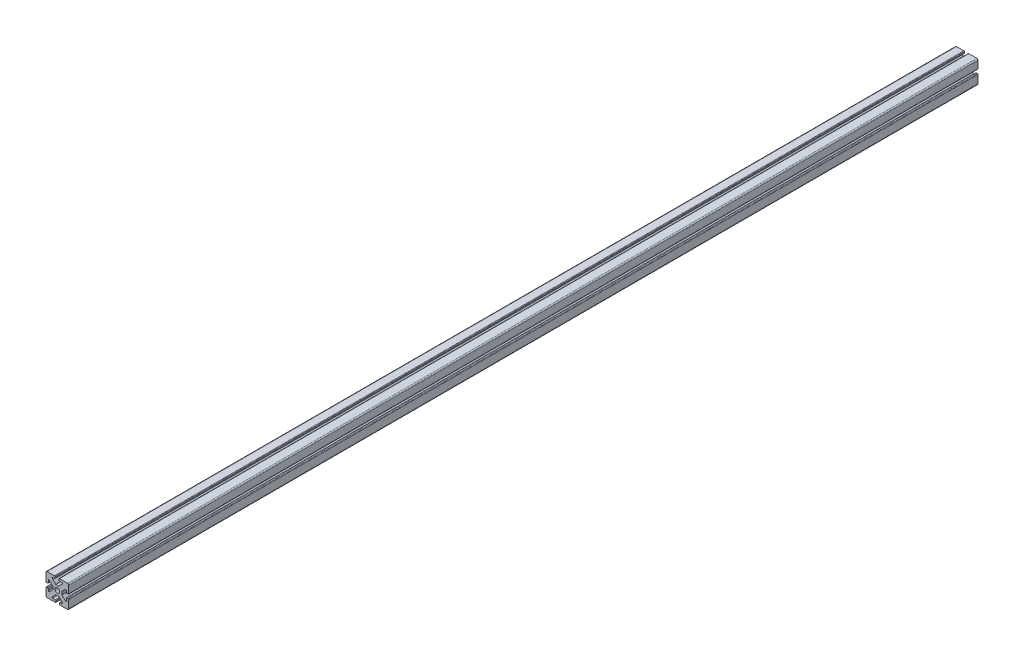
SolidWorks part; units mm, degrees
ref_plane "Front" through (0, 0, 0) normal (0, 0, 1) x (1, 0, 0)
ref_plane "Top" through (0, 0, 0) normal (0, 1, 0) x (1, 0, 0)
ref_plane "Right" through (0, 0, 0) normal (1, 0, 0) x (0, 0, -1)
sketch "草图1" plane through (0, 0, 0) normal (0, 0, 1) x (1, 0, 0)
  line L1 (-20, 20) -> (20, 20)
  line L2 (-20, 20) -> (-20, -20)
  line L3 (-20, -20) -> (20, -20)
  line L4 (20, 20) -> (20, -20)
  line L5 (-20, 20) -> (20, -20) construction
  line L6 (-20, -20) -> (20, 20) construction
  point P0 (0, 0)
  dimension "D1" = 40
extrude "凸台-拉伸1" add sketch "草图1" along normal blind 1605.02
sketch "草图2" plane through (0, 0, 1605.02) normal (0, 0, 1) x (1, 0, 0)
  circle A0 centre (0, 0) radius 4.05
  dimension "D1" = 8.1
extrude "切除-拉伸1" cut sketch "草图2" against normal blind 10000
sketch "草图4" plane through (0, 0, 1605.02) normal (0, 0, 1) x (1, 0, 0)
  line L0 (20, -20) -> (20, 20) construction
  line L1 (20, 0) -> (20, 4)
  line L2 (20, 0) -> (20, -2.652)
  line L3 (7.8769, 2.6) -> (7.8769, -2.6)
  line L4 (20, 4) -> (16, 4)
  line L5 (20, -2.652) -> (16, -2.652)
  line L6 (16, 10.5) -> (16, 4)
  line L7 (16, 10.5) -> (7.8769, 2.6)
  line L8 (16, -10.5) -> (7.8769, -2.6)
  line L9 (16, -2.652) -> (16, -10.5)
  point P11 (7.8769, 0)
  point P12 (16, 0)
extrude "切除-拉伸2" cut sketch "草图4" against normal blind 10000
fillet "圆角1" radius 1 8 edges at (16, 10.5, 802.51) (16, -10.5, 802.51) (7.8769, 2.6, 802.51) (20, -2.652, 802.51) (16, -2.652, 802.51) (20, 4, 802.51) (16, 4, 802.51) (7.8769, -2.6, 802.51)
pattern_circular "阵列(圆周)2" count 4 over 360 about axis through (0, 0, 0) along (0, 0, 1) of "切除-拉伸2"
fillet "圆角2" radius 1 8 edges at (10.5, 16, 802.51) (-10.5, 16, 802.51) (-4, 20, 802.51) (2.652, 16, 802.51) (2.652, 20, 802.51) (-2.6, 7.8769, 802.51) (-4, 16, 802.51) (2.6, 7.8769, 802.51)
fillet "圆角3" radius 1 8 edges at (-7.8769, -2.6, 802.51) (-7.8769, 2.6, 802.51) (-20, 2.652, 802.51) (-16, 10.5, 802.51) (-20, -4, 802.51) (-16, -4, 802.51) (-16, -10.5, 802.51) (-16, 2.652, 802.51)
fillet "圆角4" radius 1 8 edges at (4, -20, 802.51) (4, -16, 802.51) (10.5, -16, 802.51) (-2.652, -20, 802.51) (2.6, -7.8769, 802.51) (-2.6, -7.8769, 802.51) (-2.652, -16, 802.51) (-10.5, -16, 802.51)
fillet "圆角5" radius 2 4 edges at (-20, -20, 802.51) (20, -20, 802.51) (-20, 20, 802.51) (20, 20, 802.51)
